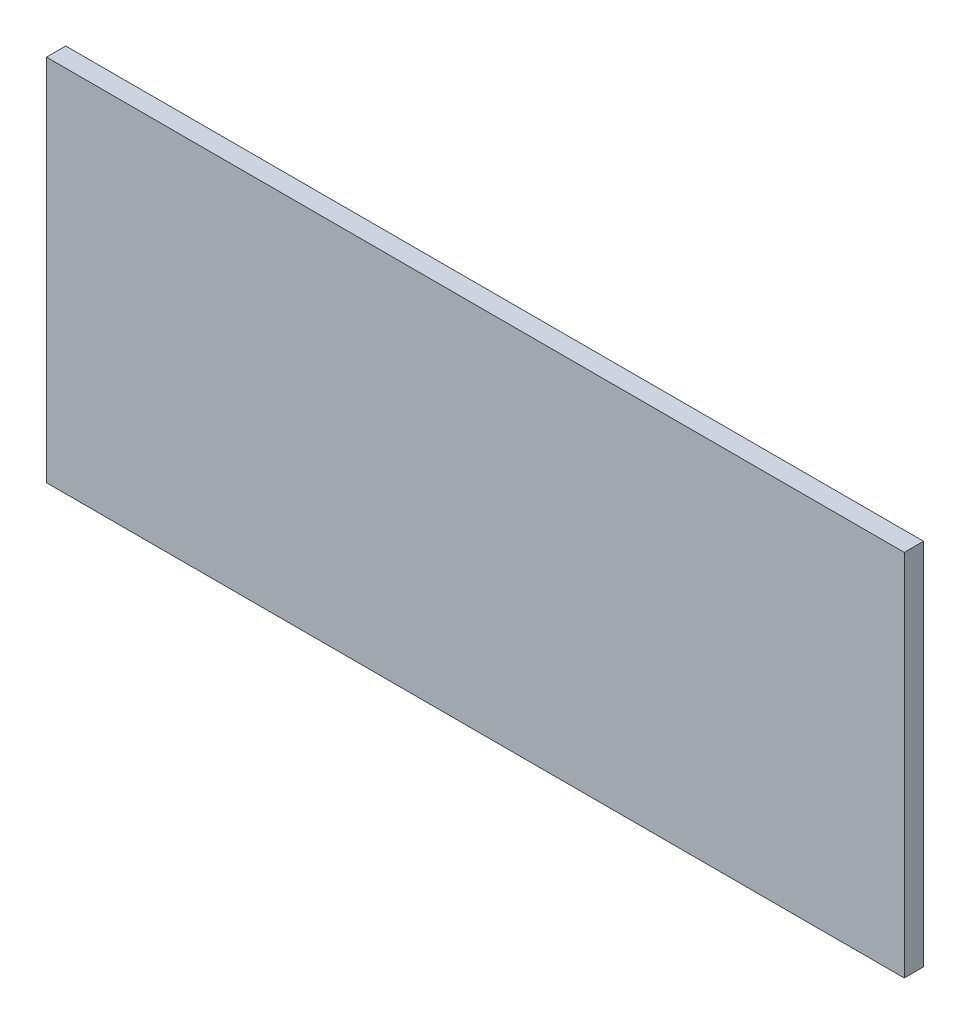
SolidWorks part; units mm, degrees
ref_plane "Front Plane" through (0, 0, 0) normal (0, 0, 1) x (1, 0, 0)
ref_plane "Top Plane" through (0, 0, 0) normal (0, 1, 0) x (1, 0, 0)
ref_plane "Right Plane" through (0, 0, 0) normal (1, 0, 0) x (0, 0, -1)
sketch "Sketch1" plane through (0, 0, 0) normal (0, 0, 1) x (1, 0, 0)
  line L1 (35.052, -15.0622) -> (-35.052, -15.0622)
  line L2 (35.052, -15.0622) -> (35.052, 15.0622)
  line L3 (35.052, 15.0622) -> (-35.052, 15.0622)
  line L4 (-35.052, -15.0622) -> (-35.052, 15.0622)
  line L5 (35.052, -15.0622) -> (-35.052, 15.0622) construction
  line L6 (35.052, 15.0622) -> (-35.052, -15.0622) construction
  point P0 (0, 0)
  dimension "D1" = 30.1244
  dimension "D2" = 70.104
extrude "Boss-Extrude1" add sketch "Sketch1" along normal blind 1.5748
sketch "Sketch2" plane through (0, 0, 1.5748) normal (0, 0, 1) x (1, 0, 0)
  line L0 (-35.052, 9.779) -> (35.052, 9.779) construction
  line L1 (-35.052, 15.0622) -> (-35.052, -15.0622) construction
  line L2 (35.052, -15.0622) -> (35.052, 15.0622) construction
  line L3 (35.052, 15.0622) -> (-35.052, 15.0622) construction
  line L4 (-25.3492, 15.0622) -> (-25.3492, -15.0622) construction
  line L5 (-35.052, -15.0622) -> (35.052, -15.0622) construction
  line L6 (-2.5654, 15.0622) -> (-2.5654, -15.0622) construction
  dimension "D1" = 5.2832
  dimension "D2" = 9.7028
  dimension "D3" = 22.7838
sketch "Sketch3" plane through (0, 0, 1.5748) normal (0, 0, 1) x (1, 0, 0)
  line L0 (-33.1724, 15.0622) -> (-33.1724, -15.0622) construction
  line L3 (35.052, 15.0622) -> (-35.052, 15.0622) construction
  line L4 (-35.052, -15.0622) -> (35.052, -15.0622) construction
  line L5 (-35.052, 15.0622) -> (-35.052, -15.0622) construction
  dimension "D1" = 1.8796
